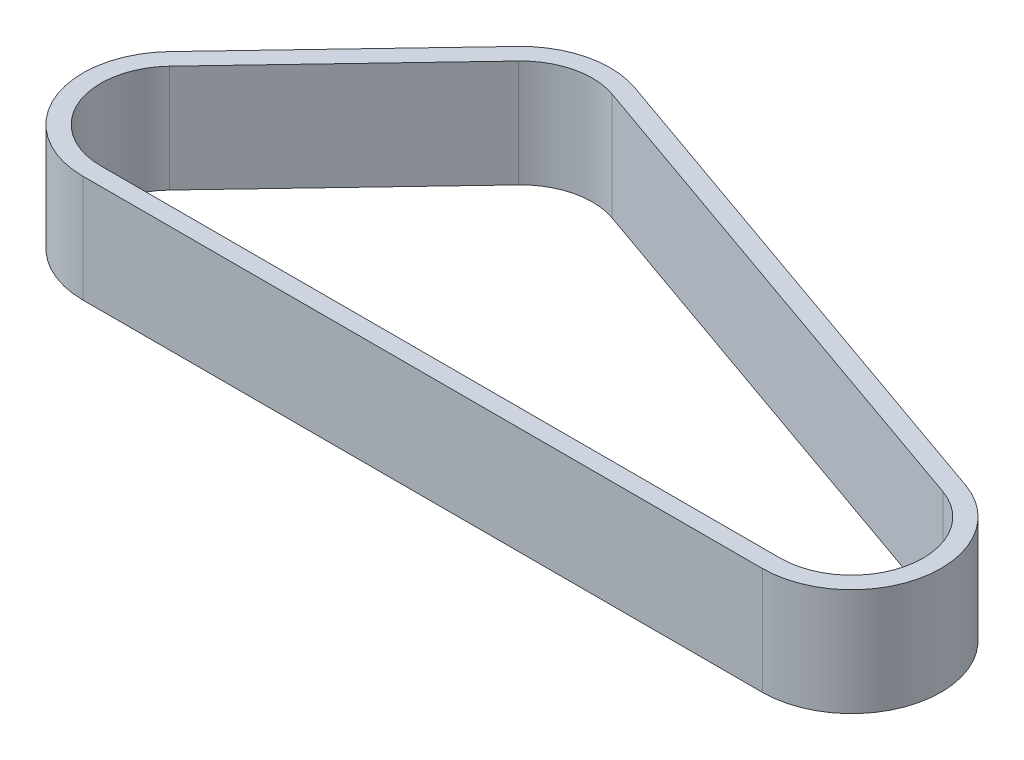
SolidWorks part; units mm, degrees
ref_plane "前视基准面" through (0, 0, 0) normal (0, 0, 1) x (1, 0, 0)
ref_plane "上视基准面" through (0, 0, 0) normal (0, 1, 0) x (1, 0, 0)
ref_plane "右视基准面" through (0, 0, 0) normal (1, 0, 0) x (0, 0, -1)
sketch "草图1" plane through (0, 0, 0) normal (0, 1, 0) x (1, 0, 0)
  line L0 (-39.2228, 73.59) -> (103.2772, 23.59)
  line L1 (-95, -25) -> (95, -25)
  line L2 (-65.625, 67.2187) -> (-113.125, 17.2187)
  line L16 (-95, 0) -> (95, 0) construction
  line L17 (-47.5, 0) -> (-47.5, 50) construction
  line L18 (-62, 63.775) -> (-109.5, 13.775)
  line L19 (-40.8782, 68.872) -> (101.6218, 18.872)
  line L20 (-95, -20) -> (95, -20)
  arc A0 (95, -25) -> (103.2772, 23.59) centre (95, 0) ccw
  arc A1 (-113.125, 17.2187) -> (-95, -25) centre (-95, 0) ccw
  arc A2 (-39.2228, 73.59) -> (-65.625, 67.2187) centre (-47.5, 50) ccw
  arc A8 (-109.5, 13.775) -> (-95, -20) centre (-95, 0) ccw
  circle A9 centre (0, 0) radius 20 construction
  arc A10 (95, -20) -> (101.6218, 18.872) centre (95, 0) ccw
  arc A11 (-40.8782, 68.872) -> (-62, 63.775) centre (-47.5, 50) ccw
  dimension "D12" = 40
  dimension "D2" = 5
  dimension "D13" = 190
  dimension "D14" = 50
extrude "凸台-拉伸1" add sketch "草图1" along normal mid plane 30
scale "Scale1" scale about centroid uniform scaling yes scale factor 2
